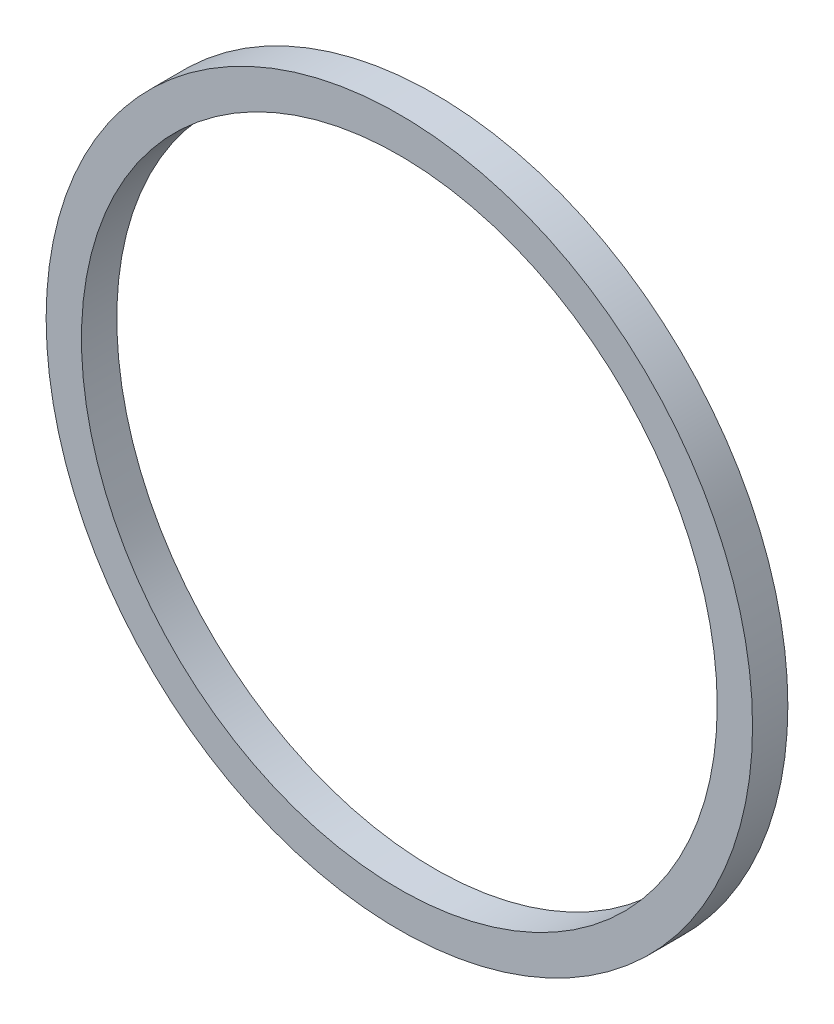
SolidWorks part; units mm, degrees
ref_plane "Front" through (0, 0, 0) normal (0, 0, 1) x (1, 0, 0)
ref_plane "Top" through (0, 0, 0) normal (0, 1, 0) x (1, 0, 0)
ref_plane "Right" through (0, 0, 0) normal (1, 0, 0) x (0, 0, -1)
other "Configuration Table"
sketch "Sketch1" plane through (0, 0, 0) normal (0, 0, 1) x (1, 0, 0)
  circle A0 centre (0, 0) radius 457.2
  circle A1 centre (0, 0) radius 508
  dimension "D1" = 914.4
  dimension "D2" = 1016
extrude "Extrude1" add sketch "Sketch1" against normal blind 50.8
